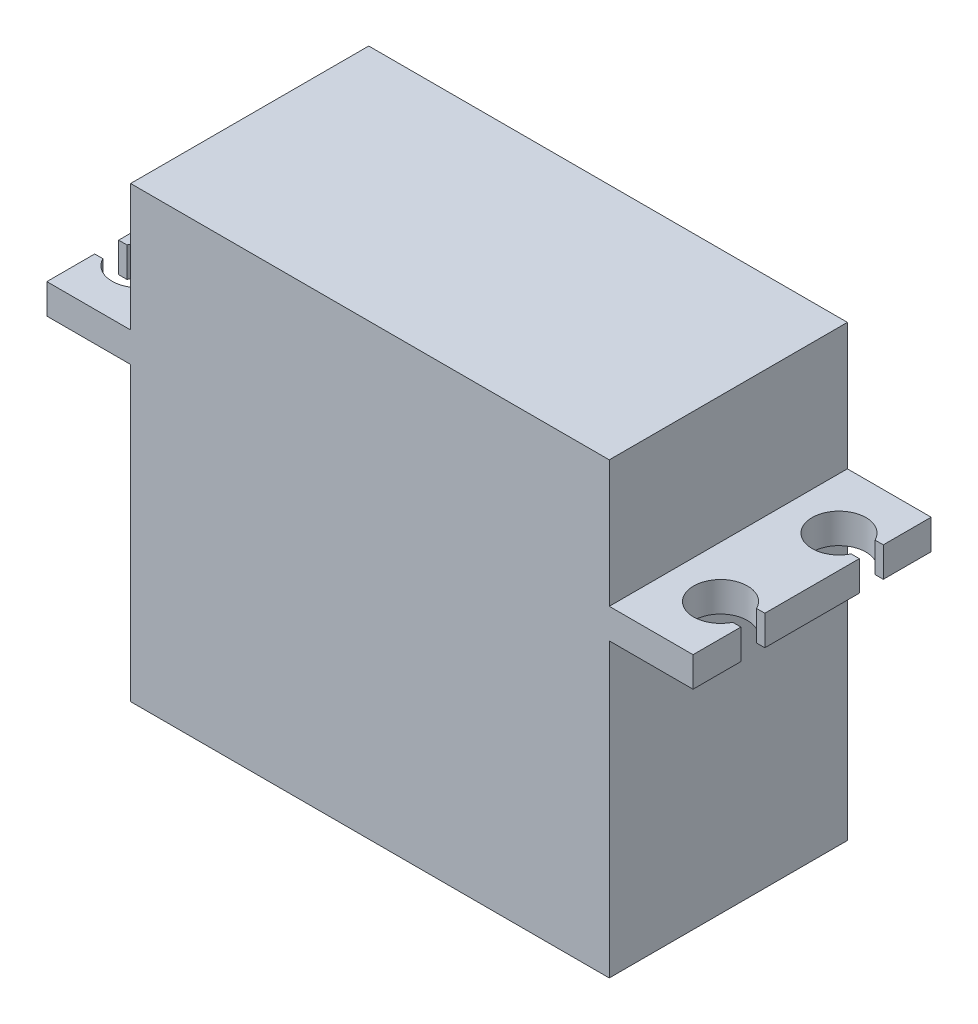
SolidWorks part; units mm, degrees
ref_plane "前视基准面" through (0, 0, 0) normal (0, 0, 1) x (1, 0, 0)
ref_plane "上视基准面" through (0, 0, 0) normal (0, 1, 0) x (1, 0, 0)
ref_plane "右视基准面" through (0, 0, 0) normal (1, 0, 0) x (0, 0, -1)
other "Configuration Table"
sketch "草图1" plane through (0, 0, 0) normal (0, 0, 1) x (1, 0, 0)
  line L1 (-20, -18.75) -> (20, -18.75)
  line L2 (-20, -18.75) -> (-20, 18.75)
  line L3 (-20, 18.75) -> (20, 18.75)
  line L4 (20, -18.75) -> (20, 18.75)
  line L5 (-20, -18.75) -> (20, 18.75) construction
  line L6 (-20, 18.75) -> (20, -18.75) construction
  point P0 (0, 0)
  dimension "D1" = 40
  dimension "D2" = 37.5
extrude "凸台-拉伸1" add sketch "草图1" along normal blind 19.9
ref_plane "基准面1" through (0, 8.15, 0) normal (0, -1, 0) x (-1, 0, 0)
sketch "草图2" plane through (0, 8.15, 0) normal (0, -1, 0) x (-1, 0, 0)
  line L0 (20, 0) -> (27, 0)
  line L1 (27, 0) -> (27, -19.9)
  line L2 (27, -19.9) -> (20, -19.9)
  line L3 (20, -19.9) -> (20, 0)
  line L4 (-20, 0) -> (-27, 0)
  line L7 (-27, 0) -> (-27, -19.9)
  line L8 (-27, -19.9) -> (-20, -19.9)
  line L9 (-20, -19.9) -> (-20, 0)
  dimension "D1" = 54
  dimension "D2" = 7
  dimension "D3" = 7
extrude "凸台-拉伸2" add sketch "草图2" along normal blind 2.5
sketch "草图3" plane through (0, 8.15, 0) normal (0, 1, 0) x (1, 0, 0)
  line L0 (-980, -9.95) -> (49020, -9.95) construction
  line L1 (20, -19.9) -> (20, 0) construction
  line L2 (0, -1019.9) -> (0, 48980.1) construction
  line L3 (20, -19.9) -> (-20, -19.9) construction
  line L4 (24.3, -14.9) -> (24.3, -5) construction
  line L5 (27, -15.9) -> (26.3156, -15.9)
  line L6 (27, 0) -> (27, -19.9) construction
  line L7 (27, -13.9) -> (26.3156, -13.9)
  line L8 (-975.7, -14.9) -> (49024.3, -14.9) construction
  line L9 (-976.8124, -5) -> (49023.1876, -5) construction
  line L10 (27, -6) -> (26.3156, -6)
  line L11 (27, -4) -> (26.3156, -4)
  line L12 (27, -4) -> (27, -6)
  line L13 (27, -15.9) -> (27, -13.9)
  line L14 (-24.3, -14.9) -> (-24.3, -5) construction
  line L15 (-27, -15.9) -> (-27, -13.9)
  line L16 (-27, -4) -> (-27, -6)
  line L17 (-27, -4) -> (-26.3156, -4)
  line L18 (-27, -6) -> (-26.3156, -6)
  line L19 (-27, -13.9) -> (-26.3156, -13.9)
  line L20 (-27, -15.9) -> (-26.3156, -15.9)
  arc A0 (26.3156, -13.9) -> (26.3156, -15.9) centre (24.3, -14.9) ccw
  arc A1 (26.3156, -4) -> (26.3156, -6) centre (24.3, -5) ccw
  arc A2 (-26.3156, -4) -> (-26.3156, -6) centre (-24.3, -5) cw
  arc A3 (-26.3156, -13.9) -> (-26.3156, -15.9) centre (-24.3, -14.9) cw
  point P5 (20, -9.95)
  point P10 (0, -19.9)
  point P14 (24.3, -9.95)
  point P29 (27, -14.9)
  point P30 (27, -5)
  dimension "D2" = 4.5
  dimension "D3" = 4.5
  dimension "D1" = 9.9
  dimension "D4" = 2
  dimension "D5" = 2
  dimension "D6" = 48.6
extrude "切除-拉伸1" cut sketch "草图3" against normal through all
